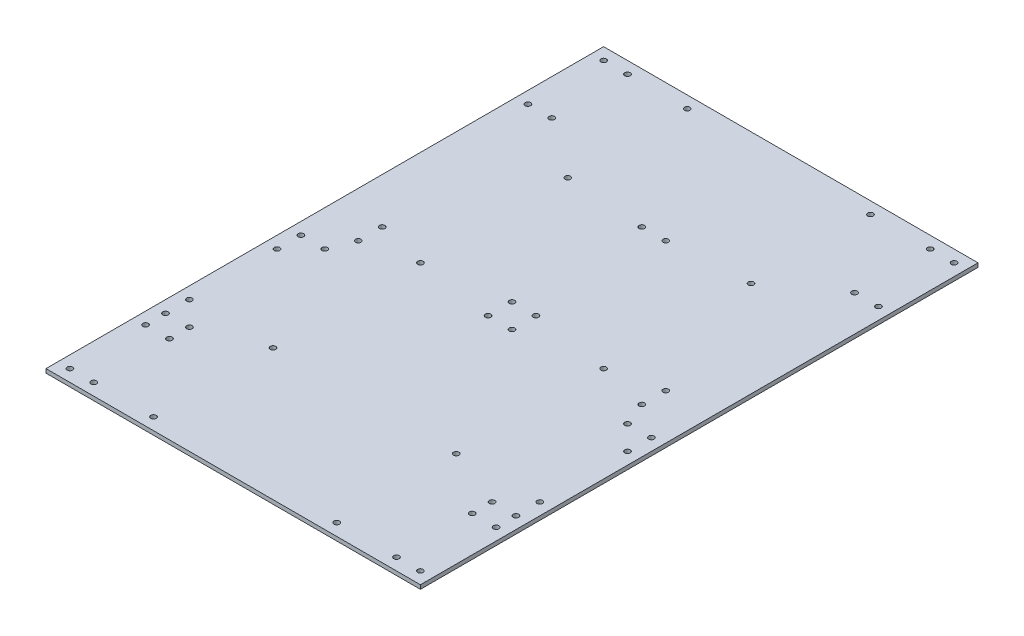
SolidWorks part; units mm, degrees
material "1060 Alloy"
ref_plane "Front Plane" through (0, 0, 0) normal (0, 0, 1) x (1, 0, 0)
ref_plane "Top Plane" through (0, 0, 0) normal (0, 1, 0) x (1, 0, 0)
ref_plane "Right Plane" through (0, 0, 0) normal (1, 0, 0) x (0, 0, -1)
sketch "Sketch1" plane through (0, 0, 0) normal (0, 1, 0) x (1, 0, 0)
  line L0 (298.45, 958.643) -> (298.45, 69.643) construction
  line L1 (0, 69.643) -> (596.9, 69.643)
  line L2 (0, 69.643) -> (0, 958.643)
  line L3 (0, 958.643) -> (596.9, 958.643)
  line L4 (596.9, 69.643) -> (596.9, 958.643)
  line L5 (0, 514.143) -> (596.9, 514.143) construction
  circle A15 centre (19.05, 939.593) radius 4.3656
  circle A17 centre (57.15, 939.593) radius 4.3656
  circle A21 centre (577.85, 939.593) radius 4.3656
  circle A26 centre (539.75, 939.593) radius 4.3656
  circle A27 centre (577.85, 88.693) radius 4.3656
  circle A28 centre (539.75, 88.693) radius 4.3656
  circle A29 centre (19.05, 88.693) radius 4.3656
  circle A30 centre (57.15, 88.693) radius 4.3656
  circle A34 centre (57.15, 209.343) radius 4.1656 construction
  circle A35 centre (19.05, 209.343) radius 4.1656 construction
  circle A36 centre (19.05, 209.343) radius 4.1656 construction
  circle A37 centre (57.15, 209.343) radius 4.1656 construction
  circle A38 centre (57.15, 209.343) radius 4.3656
  circle A39 centre (19.05, 209.343) radius 4.3656
  circle A40 centre (19.05, 818.943) radius 4.3656
  circle A41 centre (57.15, 818.943) radius 4.3656
  circle A42 centre (577.85, 209.343) radius 4.3656
  circle A43 centre (539.75, 209.343) radius 4.3656
  circle A44 centre (577.85, 818.943) radius 4.3656
  circle A45 centre (539.75, 818.943) radius 4.3656
  circle A58 centre (72.39, 533.193) radius 4.3656
  circle A59 centre (72.39, 495.093) radius 4.3656
  circle A60 centre (19.0514, 456.993) radius 4.3656
  circle A61 centre (19.05, 241.093) radius 4.3656
  circle A62 centre (279.4, 495.093) radius 4.3656
  circle A63 centre (279.4, 533.193) radius 4.3656
  circle A64 centre (279.4, 740.203) radius 4.3656
  circle A65 centre (152.4, 939.593) radius 4.3656
  circle A66 centre (152.4, 514.143) radius 4.3656
  circle A67 centre (152.4, 749.093) radius 4.3656
  circle A68 centre (152.4, 279.193) radius 4.3656
  circle A69 centre (152.4, 88.693) radius 4.3656
  circle A70 centre (444.5, 88.693) radius 4.3656
  circle A71 centre (444.5, 279.193) radius 4.3656
  circle A72 centre (317.5, 533.193) radius 4.3656
  circle A73 centre (317.5, 495.093) radius 4.3656
  circle A74 centre (577.85, 241.093) radius 4.3656
  circle A75 centre (577.8486, 456.993) radius 4.3656
  circle A76 centre (524.51, 495.093) radius 4.3656
  circle A77 centre (524.51, 533.193) radius 4.3656
  circle A78 centre (444.5, 514.143) radius 4.3656
  circle A79 centre (317.5, 740.203) radius 4.3656
  circle A80 centre (444.5, 749.093) radius 4.3656
  circle A81 centre (444.5, 939.593) radius 4.3656
  circle A82 centre (19.05, 279.193) radius 4.3656
  circle A83 centre (57.15, 241.093) radius 4.3656
  circle A84 centre (577.85, 279.193) radius 4.3656
  circle A85 centre (539.75, 241.093) radius 4.3656
  circle A86 centre (19.0514, 418.893) radius 4.3656
  circle A87 centre (57.1514, 456.993) radius 4.3656
  circle A88 centre (577.8486, 418.893) radius 4.3656
  circle A89 centre (539.7486, 456.993) radius 4.3656
  dimension "D4" = 8.7312
  dimension "D1" = 596.9
  dimension "D2" = 19.05
  dimension "D3" = 19.05
  dimension "D5" = 38.1
  dimension "D7" = 139.7
  dimension "D10" = 889
  dimension "D11" = 19.05
  dimension "D15" = 19.0514
  dimension "D16" = 57.15
  dimension "D19" = 19.05
  dimension "D20" = 19.05
  dimension "D21" = 171.45
  dimension "D22" = 19.05
  dimension "D6" = 19.05
  dimension "D24" = 19.05
  dimension "D27" = 19.05
  dimension "D28" = 19.05
  dimension "D29" = 19.05
  dimension "D32" = 152.4
  dimension "D35" = 209.55
  dimension "D30" = 226.06
  dimension "D17" = 226.06
  dimension "D18" = 226.06
  dimension "D37" = 38.1
  dimension "D41" = 38.1
  dimension "D43" = 38.1
extrude "Boss-Extrude1" add sketch "Sketch1" along normal blind 6.35
equation "\"D32@Sketch1\"=6"
